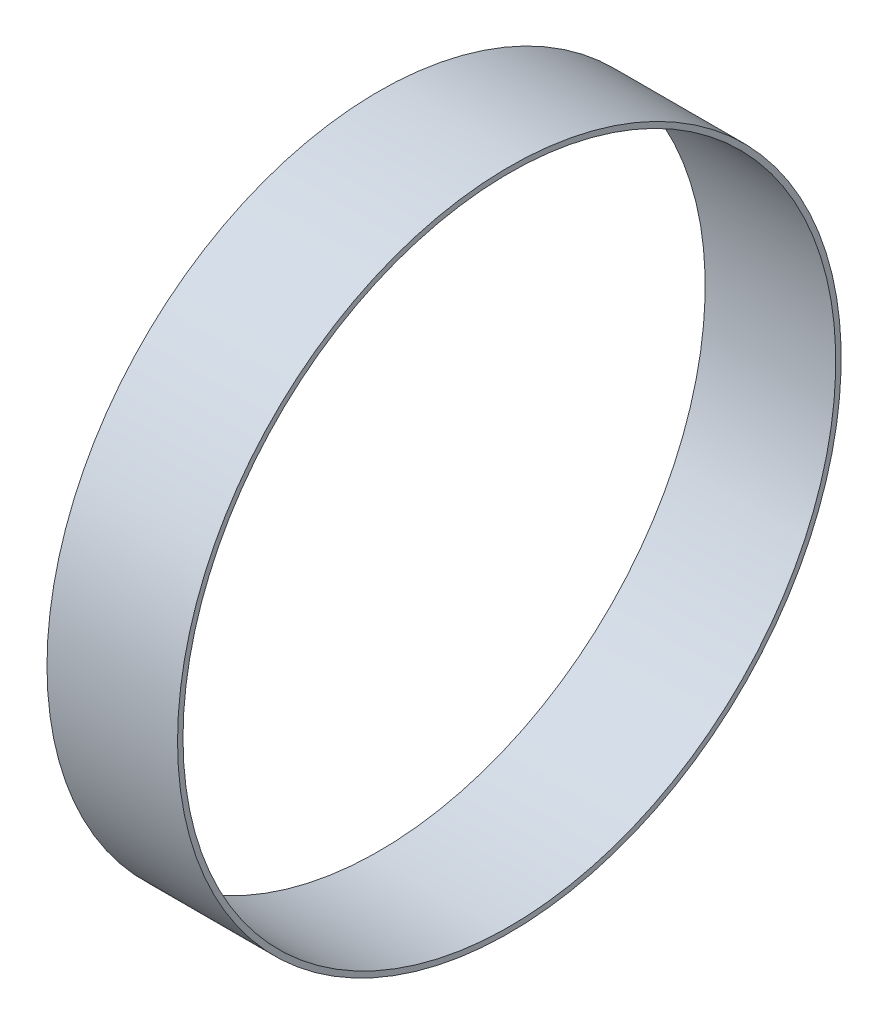
SolidWorks part; units mm, degrees
ref_plane "Front Plane" through (0, 0, 0) normal (0, 0, 1) x (1, 0, 0)
ref_plane "Top Plane" through (0, 0, 0) normal (0, 1, 0) x (1, 0, 0)
ref_plane "Right Plane" through (0, 0, 0) normal (1, 0, 0) x (0, 0, -1)
sketch "Sketch1" plane through (0, 0, 0) normal (1, 0, 0) x (0, 0, -1)
  line L0 (-190.5, 0) -> (-193.675, 0) construction
  circle A0 centre (0, 0) radius 193.675
  circle A1 centre (0, 0) radius 190.5
  dimension "D2" = 381
  dimension "D1" = 3.175
extrude "Boss-Extrude1" add sketch "Sketch1" along normal blind 76.2
